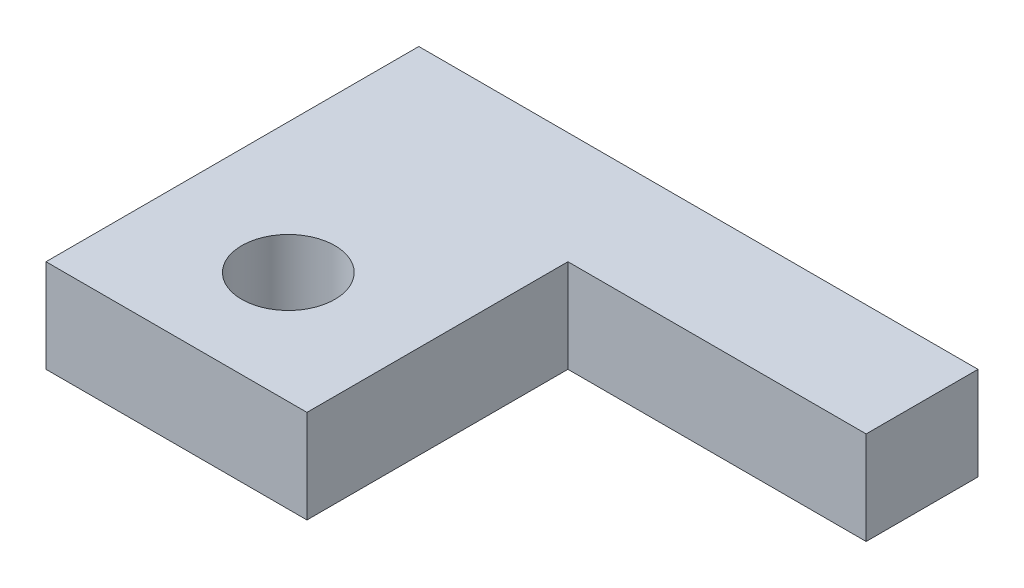
SolidWorks part; units mm, degrees
ref_plane "Front Plane" through (0, 0, 0) normal (0, 0, 1) x (1, 0, 0)
ref_plane "Top Plane" through (0, 0, 0) normal (0, 1, 0) x (1, 0, 0)
ref_plane "Right Plane" through (0, 0, 0) normal (1, 0, 0) x (0, 0, -1)
sketch "Sketch4" plane through (0, 0, 0) normal (0, 1, 0) x (1, 0, 0)
  line L9 (0, 0) -> (-7, 0)
  line L10 (0, 0) -> (0, 7)
  line L11 (0, 7) -> (-7, 7)
  line L12 (-7, 0) -> (-7, 7)
  line L13 (-7, 7) -> (8, 7)
  line L14 (-7, 7) -> (-7, 10)
  line L15 (-7, 10) -> (8, 10)
  line L16 (8, 7) -> (8, 10)
  circle A1 centre (-3.5, 3) radius 1.25
  point P13 (-4.0904, 6)
  dimension "D2" = 10
  dimension "D5" = 2.5
  dimension "D1" = 7
  dimension "D3" = 3
  dimension "D4" = 15
  dimension "D6" = 3.5
  dimension "D7" = 3
extrude "Boss-Extrude2" add sketch "Sketch4" along normal blind 2.5 contours L12 L9 L10 L11 A1 | L13 L16 L15 L14 L11
